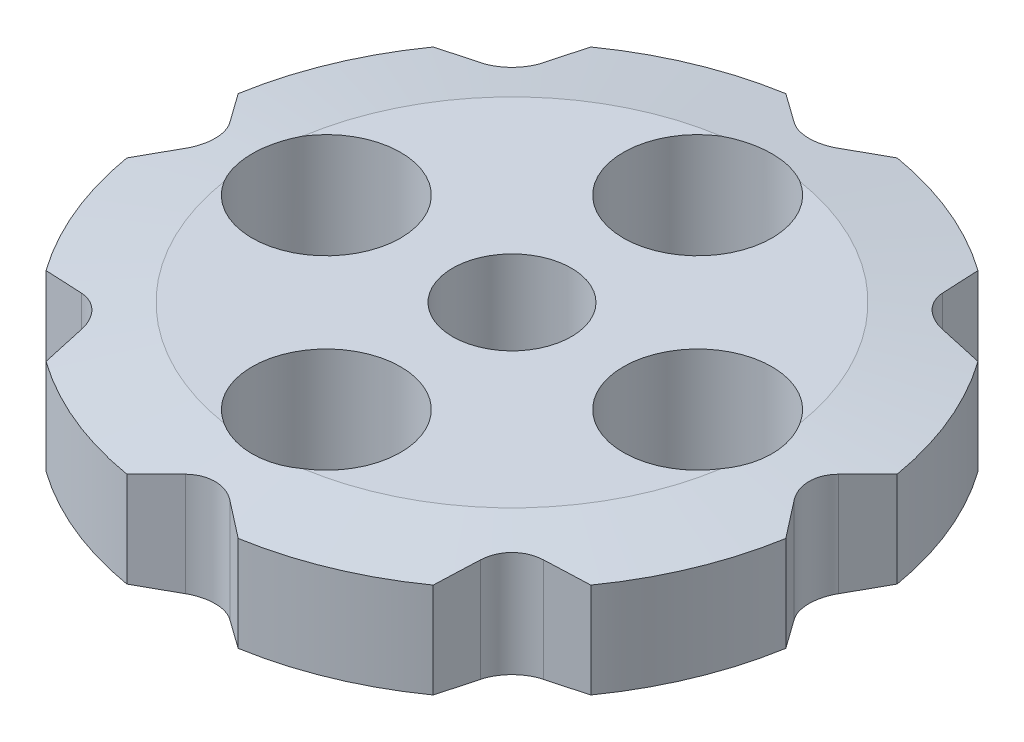
SolidWorks part; units mm, degrees
ref_plane "前视基准面" through (0, 0, 0) normal (0, 0, 1) x (1, 0, 0)
ref_plane "上视基准面" through (0, 0, 0) normal (0, 1, 0) x (1, 0, 0)
ref_plane "右视基准面" through (0, 0, 0) normal (1, 0, 0) x (0, 0, -1)
sketch "草图1" plane through (0, 0, 0) normal (0, 1, 0) x (1, 0, 0)
  line L0 (1.0583, 1.2) -> (-1.0583, 1.2)
  circle A0 centre (0, 0) radius 9
  circle A1 centre (0, 0) radius 1.6
  dimension "D1" = 3.2
  dimension "D2" = 1.2
  dimension "D3" = 18
extrude "凸台-拉伸1" add sketch "草图1" along normal blind 3.2 contours L0 A1 | A0 A1
sketch "草图4" plane through (0, 3.2, 0) normal (0, 1, 0) x (1, 0, 0)
  line L0 (-0.5995, 8.1996) -> (-1.5, 8.8741)
  line L1 (0, 9) -> (0, 0) construction
  line L2 (0.5995, 8.1996) -> (1.5, 8.8741)
  circle A0 centre (0, 0) radius 9 construction
  circle A1 centre (0, 9) radius 1
  circle A2 centre (0, 0) radius 9
  dimension "D2" = 1.5
  dimension "D1" = 2
  dimension "D3" = 1.5
extrude "切除-拉伸2" cut sketch "草图4" against normal up to next
pattern_circular "阵列(圆周)1" count 8 over 360 about axis through (0, 0, 0) along (0, 1, 0) of "切除-拉伸2"
sketch "草图3" plane through (0, 3.2, 0) normal (0, 1, 0) x (1, 0, 0)
  circle A0 centre (0, 5) radius 2
  dimension "D1" = 4
  dimension "D3" = 5
extrude "切除-拉伸1" cut sketch "草图3" against normal up to next
pattern_circular "阵列(圆周)2" count 4 over 360 about axis through (0, 0, 0) along (0, 1, 0) of "切除-拉伸1"
sketch "草图5" plane through (0, 0, 0) normal (1, 0, 0) x (0, 0, -1)
  line L0 (9.3741, 2.8284) -> (6.7788, 3.2)
  line L2 (6.2219, 3.2) -> (7.3356, 3.2) construction
  line L3 (6.7788, 3.2) -> (9.3741, 3.2)
  line L4 (8.8741, 3.2) -> (7.3356, 3.2) construction
  line L5 (9.3741, 3.2) -> (9.3741, 2.8284)
  line L6 (8.8741, 0) -> (8.8741, 3.2) construction
  line L7 (8.8741, 3.2) -> (8.8741, 2.9) construction
  dimension "D1" = 0.3
  dimension "D2" = 0.5
ref_axis "基准轴1" through (0, 3.2, 0) along (0, -1, 0)
revolve "切除-旋转1" cut sketch "草图5" angle 360 about axis through (0, 3.2, 0) along (0, -1, 0)
ref_plane "基准面1" through (0, 1.6, 0) normal (0, 1, 0) x (1, 0, 0)
mirror "镜向1" about plane through (0, 1.6, 0) normal (0, 1, 0) of "切除-旋转1"
sketch "草图6" plane through (0, 3.2, 0) normal (0, 1, 0) x (1, 0, 0)
  circle A0 centre (0, 0) radius 1.6
extrude "切除-拉伸3" cut sketch "草图6" against normal up to next
